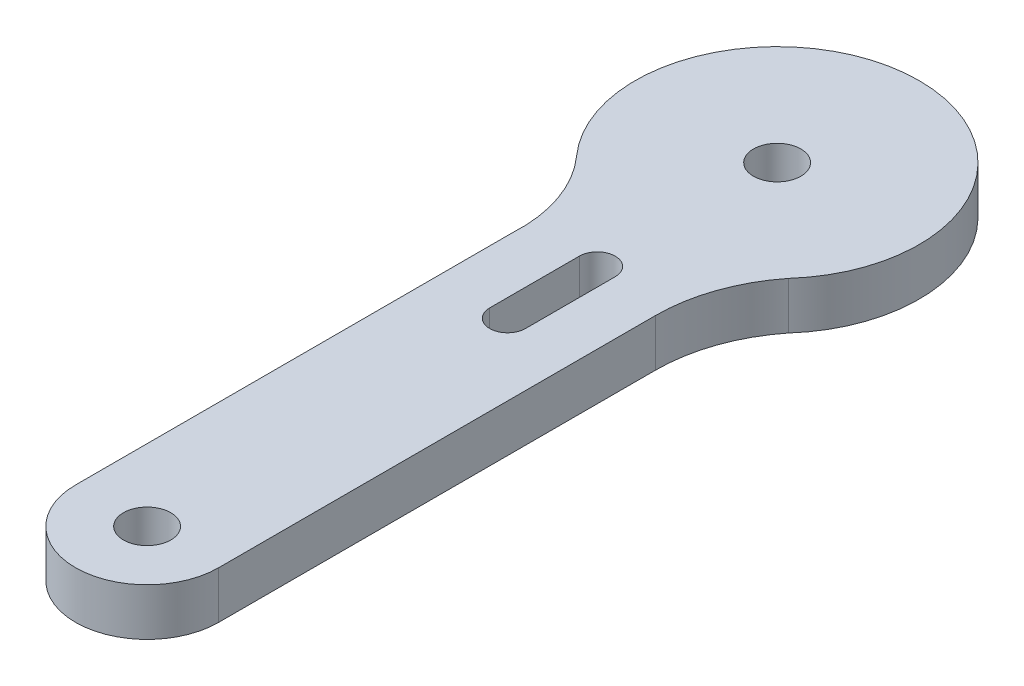
SolidWorks part; units mm, degrees
material "Acrylic (Medium-high impact)"
ref_plane "Front Plane" through (0, 0, 0) normal (0, 0, 1) x (1, 0, 0)
ref_plane "Top Plane" through (0, 0, 0) normal (0, 1, 0) x (1, 0, 0)
ref_plane "Right Plane" through (0, 0, 0) normal (1, 0, 0) x (0, 0, -1)
sketch "Sketch1" plane through (0, 0, 0) normal (0, 1, 0) x (1, 0, 0)
  line L0 (6.326, 13.7306) -> (-7.3069, 13.7306) construction
  line L1 (4.12, 7.3855) -> (4.12, -20.7355)
  line L2 (-5.101, -20.7355) -> (-5.101, 7.3855)
  line L3 (-1.6431, 8.2469) -> (-1.6431, 2.4733)
  line L4 (0.6621, 2.4733) -> (0.6621, 8.2469)
  arc A0 (6.326, 13.7306) -> (-7.3069, 13.7306) centre (-0.4905, 19.8255) ccw
  arc A1 (-7.3069, 13.7306) -> (-5.101, 7.3855) centre (-13.8141, 7.9122) cw
  arc A2 (4.12, 7.3855) -> (6.326, 13.7306) centre (14.3483, 7.3855) cw
  arc A3 (-1.6431, 8.2469) -> (0.6621, 8.2469) centre (-0.4905, 8.2469) cw
  arc A4 (-1.6431, 2.4733) -> (0.6621, 2.4733) centre (-0.4905, 2.4733) ccw
  arc A5 (-5.101, -20.7355) -> (4.12, -20.7355) centre (-0.4905, -20.7355) ccw
  circle A6 centre (-0.4905, -20.7355) radius 1.524
  circle A7 centre (-0.4905, 19.8255) radius 1.524
  point P9 (6.326, 13.7306)
  point P10 (-0.4905, -20.7355)
  point P23 (-0.4905, 19.8255)
  dimension "D1" = 18.288
  dimension "D2" = 3.048
extrude "Boss-Extrude1" add sketch "Sketch1" along normal blind 3.048
